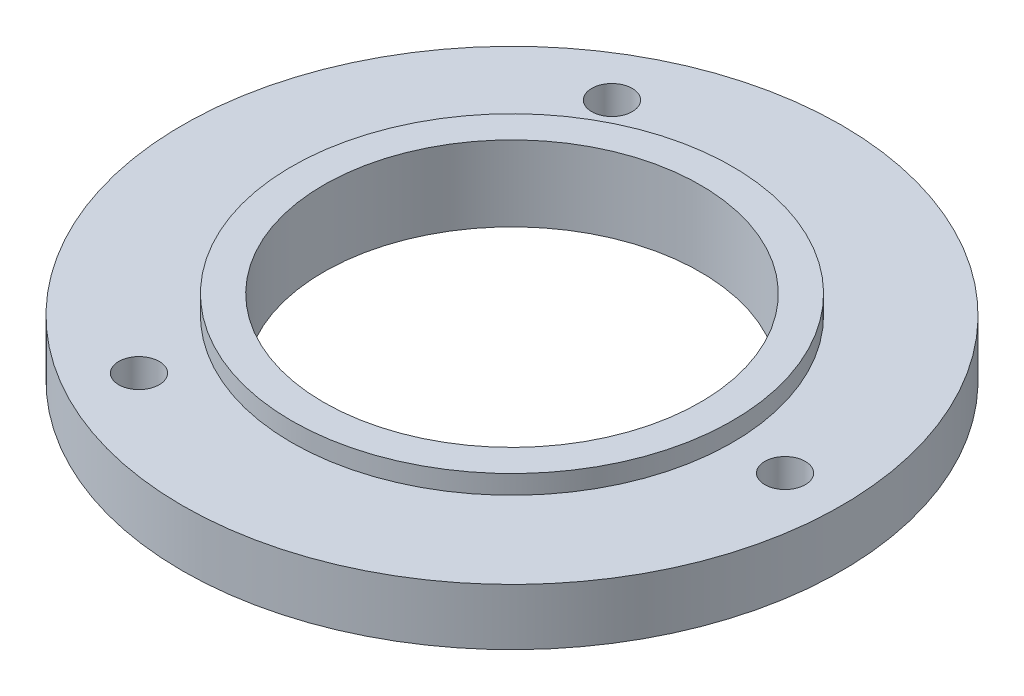
SolidWorks part; units mm, degrees
material "ABS"
ref_plane "前视基准面" through (0, 0, 0) normal (0, 0, 1) x (1, 0, 0)
ref_plane "上视基准面" through (0, 0, 0) normal (0, 1, 0) x (1, 0, 0)
ref_plane "右视基准面" through (0, 0, 0) normal (1, 0, 0) x (0, 0, -1)
sketch "草图1" plane through (0, 0, 0) normal (0, 1, 0) x (1, 0, 0)
  circle A0 centre (0, 0) radius 20
  circle A1 centre (0, 0) radius 35
  dimension "D1" = 40
  dimension "D2" = 70
extrude "凸台-拉伸1" add sketch "草图1" along normal blind 6
sketch "草图2" plane through (0, 6, 0) normal (0, 1, 0) x (1, 0, 0)
  line L0 (-35, 0) -> (35, 0) construction
  line L1 (0, 35) -> (0, -35) construction
  circle A0 centre (0, 0) radius 35 construction
  circle A1 centre (0, 0) radius 29 construction
  circle A2 centre (29, 0) radius 2.15
  circle A3 centre (-14.5, -25.1147) radius 2.15
  circle A4 centre (-14.5, 25.1147) radius 2.15
  dimension "D1" = 58
  dimension "D2" = 4.3
  dimension "D3" = 3
extrude "切除-拉伸1" cut sketch "草图2" against normal blind 70
fillet "圆角2" radius 2 3 edges at (-14.5, 0, 27.2647) (29, 0, 2.15) (-14.5, 0, -22.9647)
sketch "草图3" plane through (0, 6, 0) normal (0, 1, 0) x (1, 0, 0)
  circle A0 centre (0, 0) radius 23.4
  circle A1 centre (0, 0) radius 20
  dimension "D1" = 46.8
extrude "凸台-拉伸2" add sketch "草图3" along normal blind 2
